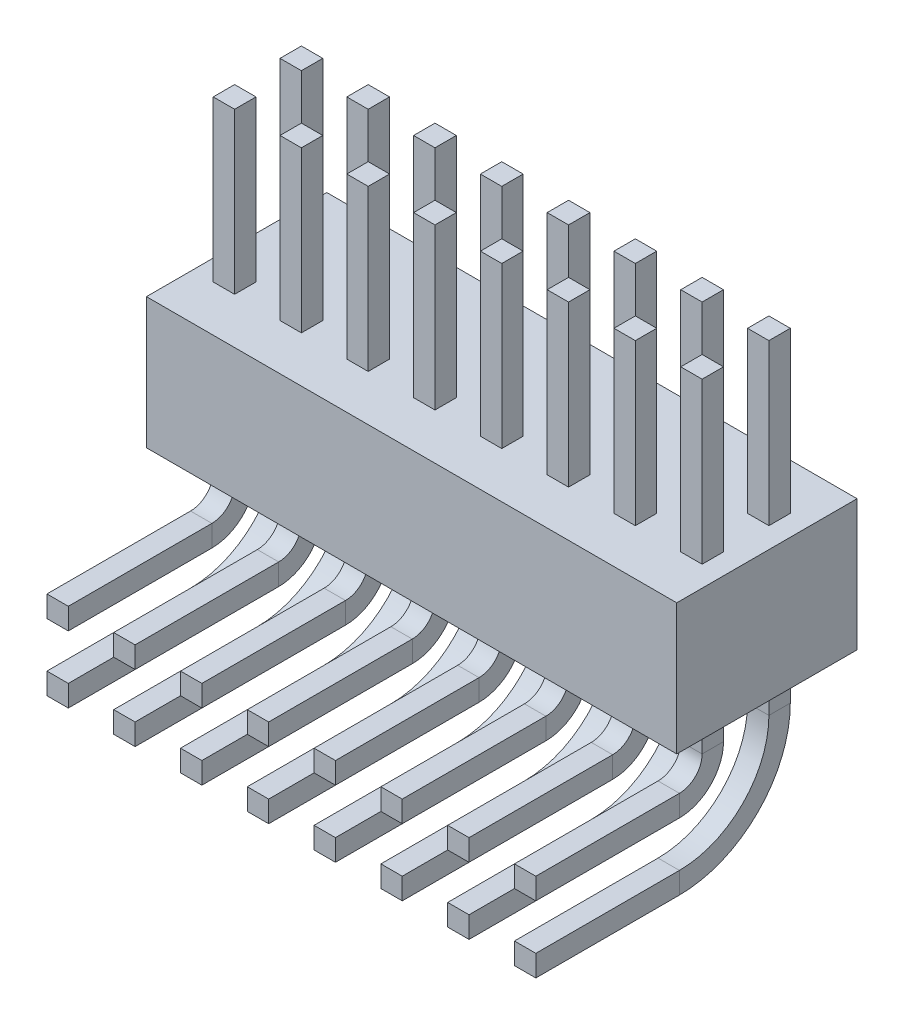
SolidWorks part; units mm, degrees
ref_plane "Front Plane" through (0, 0, 0) normal (0, 0, 1) x (1, 0, 0)
ref_plane "Top Plane" through (0, 0, 0) normal (0, 1, 0) x (1, 0, 0)
ref_plane "Right Plane" through (0, 0, 0) normal (1, 0, 0) x (0, 0, -1)
sketch "Sketch1" plane through (0, 0, 0) normal (0, 1, 0) x (1, 0, 0)
  line L1 (-5.0419, -1.7145) -> (5.0419, -1.7145)
  line L2 (-5.0419, -1.7145) -> (-5.0419, 1.7145)
  line L3 (-5.0419, 1.7145) -> (5.0419, 1.7145)
  line L4 (5.0419, -1.7145) -> (5.0419, 1.7145)
  line L5 (-5.0419, -1.7145) -> (5.0419, 1.7145) construction
  line L6 (-5.0419, 1.7145) -> (5.0419, -1.7145) construction
  point P0 (0, 0)
  dimension "D1" = 10.0838
  dimension "D2" = 3.429
extrude "Boss-Extrude1" add sketch "Sketch1" along normal mid plane 2.4892
ref_plane "Plane1" through (4.445, 0, 0) normal (1, 0, 0) x (0, 0, -1)
sketch "Sketch2" plane through (4.445, 0, 0) normal (1, 0, 0) x (0, 0, -1)
  line L0 (-0.635, 4.2926) -> (-0.635, -1.8796)
  line L1 (-1.27, -2.5146) -> (-4.0005, -2.5146)
  line L2 (0.635, 4.2926) -> (0.635, -3.1496)
  line L3 (0, -3.7846) -> (-4.0005, -3.7846)
  line L4 (-1.7145, -1.2446) -> (1.7145, -1.2446) construction
  line L5 (-1.7145, 1.2446) -> (-1.7145, -1.2446) construction
  line L6 (-1.7145, 1.2446) -> (1.7145, 1.2446) construction
  arc A0 (0.635, -3.1496) -> (0, -3.7846) centre (0, -3.1496) cw
  arc A1 (-0.635, -1.8796) -> (-1.27, -2.5146) centre (-1.27, -1.8796) cw
  dimension "D7" = 0.635
  dimension "D1" = 1.27
  dimension "D2" = 1.27
  dimension "D3" = 1.27
  dimension "D4" = 0.635
  dimension "D5" = 2.286
  dimension "D6" = 3.048
ref_plane "Plane2" through (0, 4.2926, 0) normal (0, 1, 0) x (1, 0, 0)
sketch "Sketch3" plane through (0, 4.2926, 0) normal (0, 1, 0) x (1, 0, 0)
  line L0 (4.445, -1.27) -> (4.445, -0.635) construction
  line L1 (4.2418, -0.8382) -> (4.6482, -0.8382)
  line L2 (4.2418, -0.8382) -> (4.2418, -0.4318)
  line L3 (4.2418, -0.4318) -> (4.6482, -0.4318)
  line L4 (4.6482, -0.8382) -> (4.6482, -0.4318)
  line L5 (4.2418, -0.8382) -> (4.6482, -0.4318) construction
  line L6 (4.2418, -0.4318) -> (4.6482, -0.8382) construction
  line L7 (4.445, 0) -> (4.445, -4.0005) construction
  line L8 (4.445, 0) -> (4.445, 0.635) construction
  line L15 (4.445, -1.3691) -> (4.445, 1.3691) construction
  line L16 (4.2418, 0.4318) -> (4.6482, 0.4318)
  line L17 (4.2418, 0.4318) -> (4.2418, 0.8382)
  line L18 (4.2418, 0.8382) -> (4.6482, 0.8382)
  line L19 (4.6482, 0.4318) -> (4.6482, 0.8382)
  line L20 (4.2418, 0.4318) -> (4.6482, 0.8382) construction
  line L21 (4.2418, 0.8382) -> (4.6482, 0.4318) construction
  point P0 (4.445, -0.635)
  point P16 (4.445, 0.635)
  dimension "D1" = 0.4064
  dimension "D2" = 1.27
sweep "Sweep1" add profiles "Sketch3" path "Sketch2"
pattern_linear "LPattern1" count 8 spacing 1.27 along (-1, 0, 0) of "Sweep1"
